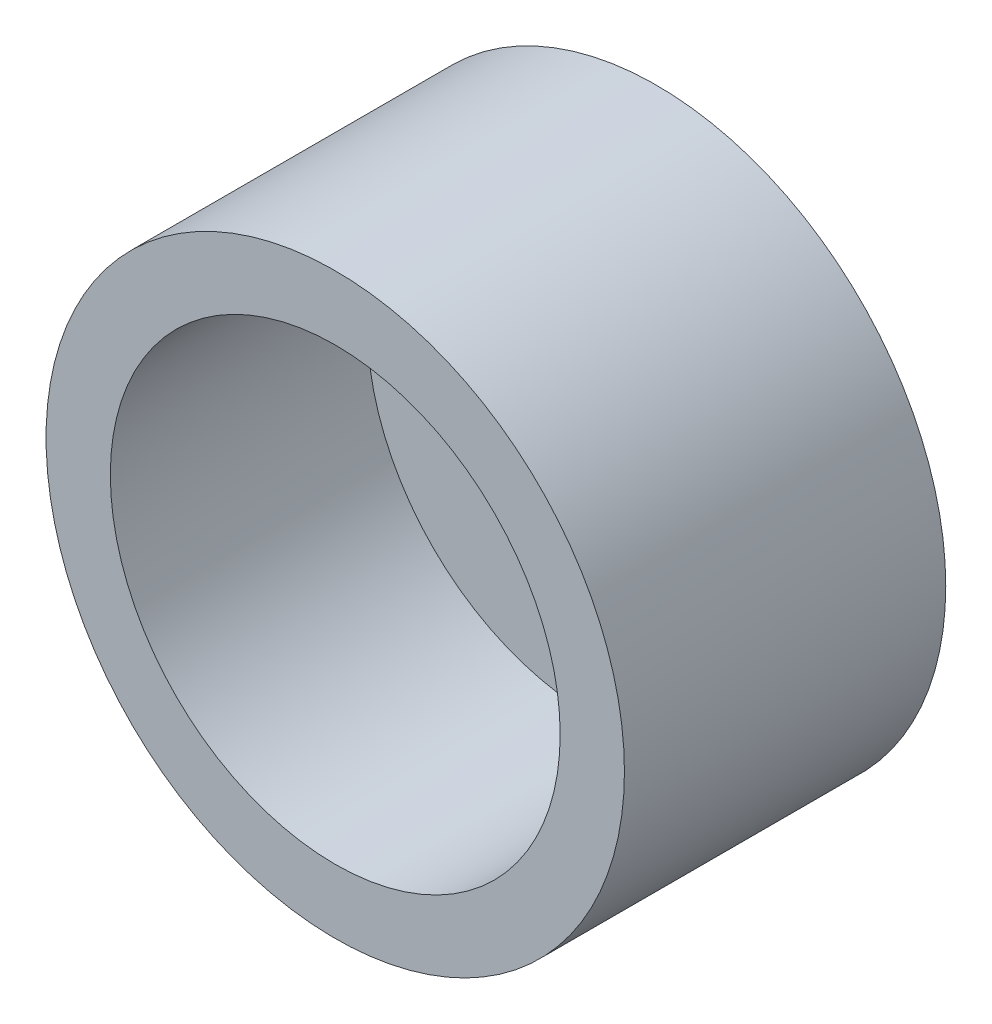
SolidWorks part; units mm, degrees
ref_plane "Alzado" through (0, 0, 0) normal (0, 0, 1) x (1, 0, 0)
ref_plane "Planta" through (0, 0, 0) normal (0, 1, 0) x (1, 0, 0)
ref_plane "Vista lateral" through (0, 0, 0) normal (1, 0, 0) x (0, 0, -1)
sketch "Croquis1" plane through (0, 0, 0) normal (0, 0, 1) x (1, 0, 0)
  circle A0 centre (0, 0) radius 9
  dimension "D1" = 18
extrude "Saliente-Extruir1" add sketch "Croquis1" along normal blind 10
shell "Vaciado1" thickness 2
